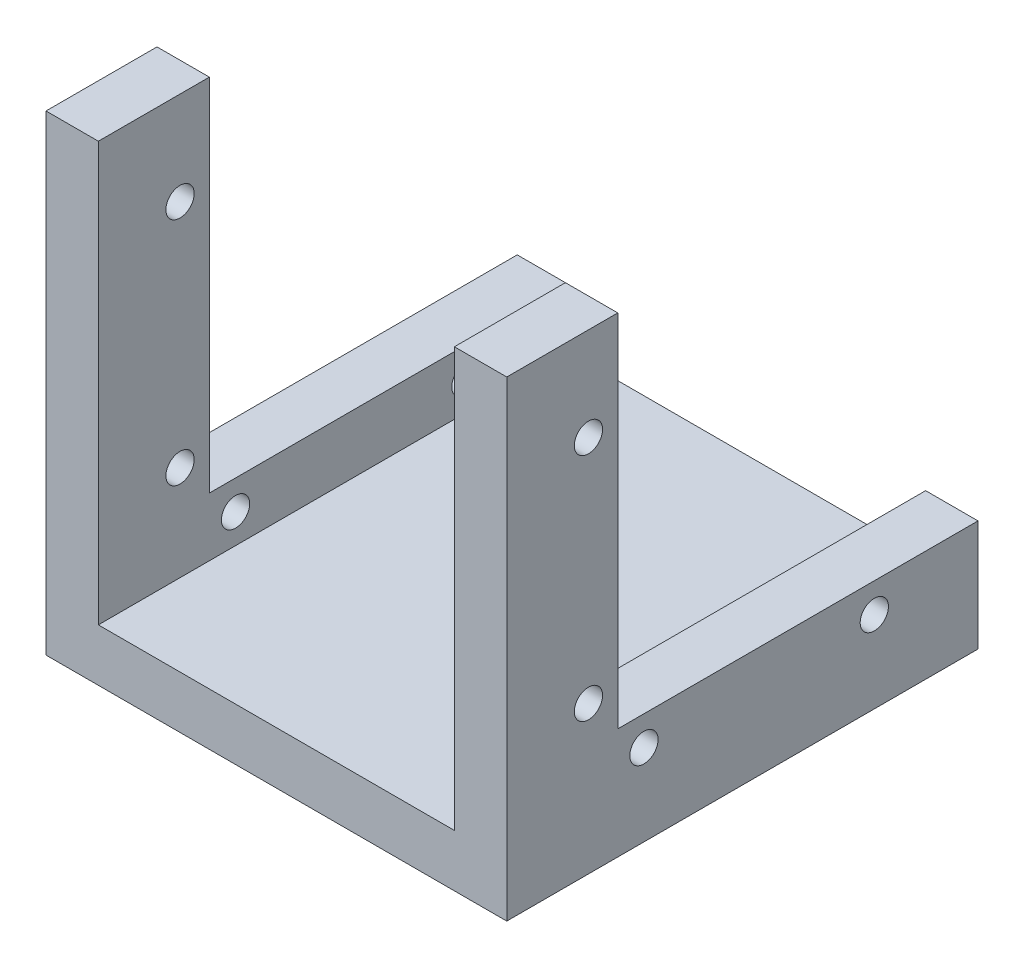
SolidWorks part; units mm, degrees
material "Aluminium 1050"
ref_plane "Front Plane" through (0, 0, 0) normal (0, 0, 1) x (1, 0, 0)
ref_plane "Top Plane" through (0, 0, 0) normal (0, 1, 0) x (1, 0, 0)
ref_plane "Right Plane" through (0, 0, 0) normal (1, 0, 0) x (0, 0, -1)
sketch "Sketch1" plane through (0, 0, 0) normal (0, 0, 1) x (1, 0, 0)
  line L0 (0, 0) -> (44, 0)
  line L1 (44, 0) -> (44, 45)
  line L2 (44, 45) -> (39, 45)
  line L3 (39, 45) -> (39, 5)
  line L4 (39, 5) -> (5, 5)
  line L5 (5, 5) -> (5, 45)
  line L6 (5, 45) -> (0, 45)
  line L7 (0, 45) -> (0, 0)
  dimension "D1" = 44
  dimension "D2" = 45
  dimension "D3" = 45
  dimension "D4" = 5
  dimension "D5" = 5
  dimension "D6" = 40
extrude "Boss-Extrude1" add sketch "Sketch1" along normal blind 45
sketch "Sketch3" plane through (5, 0, 0) normal (1, 0, 0) x (0, 0, -1)
  line L0 (-34.4, 10.6) -> (-34.4, 45)
  line L1 (-45, 45) -> (0, 45) construction
  line L3 (-34.4, 10.6) -> (0, 10.6)
  line L5 (-34.4, 45) -> (0, 45)
  line L6 (0, 45) -> (0, 10.6)
  circle A2 centre (-37.2, 36.1) radius 1.35
  circle A3 centre (-37.2, 14.1) radius 1.35
  circle A4 centre (-31.9, 7.8) radius 1.35
  circle A5 centre (-9.9, 7.8) radius 1.35
extrude "Cut-Extrude1" cut sketch "Sketch3" against normal through all both and the other way through all
